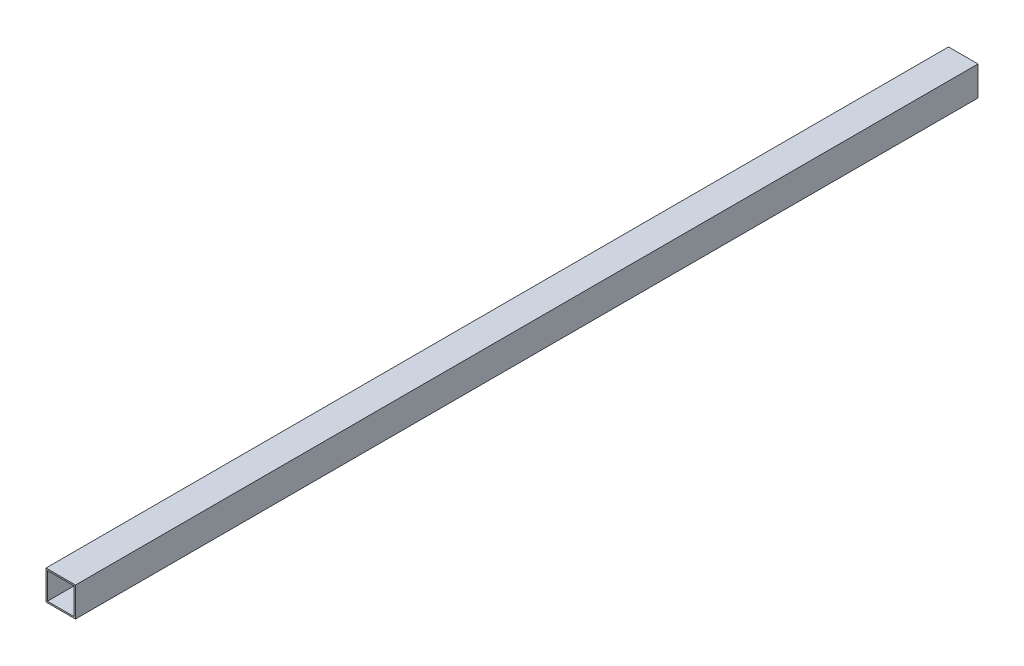
SolidWorks part; units mm, degrees
ref_plane "Front Plane" through (0, 0, 0) normal (0, 0, 1) x (1, 0, 0)
ref_plane "Top Plane" through (0, 0, 0) normal (0, 1, 0) x (1, 0, 0)
ref_plane "Right Plane" through (0, 0, 0) normal (1, 0, 0) x (0, 0, -1)
sketch "Sketch1" plane through (0, 0, 0) normal (0, 0, 1) x (1, 0, 0)
  line L0 (0, 0) -> (780, 0) construction
  line L1 (-12.5, -12.5) -> (12.5, -12.5)
  line L2 (-12.5, -12.5) -> (-12.5, 12.5)
  line L3 (-12.5, 12.5) -> (12.5, 12.5)
  line L4 (12.5, -12.5) -> (12.5, 12.5)
  line L5 (-12.5, -12.5) -> (12.5, 12.5) construction
  line L6 (-12.5, 12.5) -> (12.5, -12.5) construction
  line L7 (-11.3, 11.3) -> (11.3, 11.3)
  line L8 (11.3, -11.3) -> (11.3, 11.3)
  line L9 (-11.3, -11.3) -> (11.3, -11.3)
  line L10 (-11.3, -11.3) -> (-11.3, 11.3)
  point P0 (0, 0)
  dimension "D1" = 25
  dimension "D2" = 25
  dimension "D3" = 1.2
extrude "Boss-Extrude1" add sketch "Sketch1" along normal blind 765
